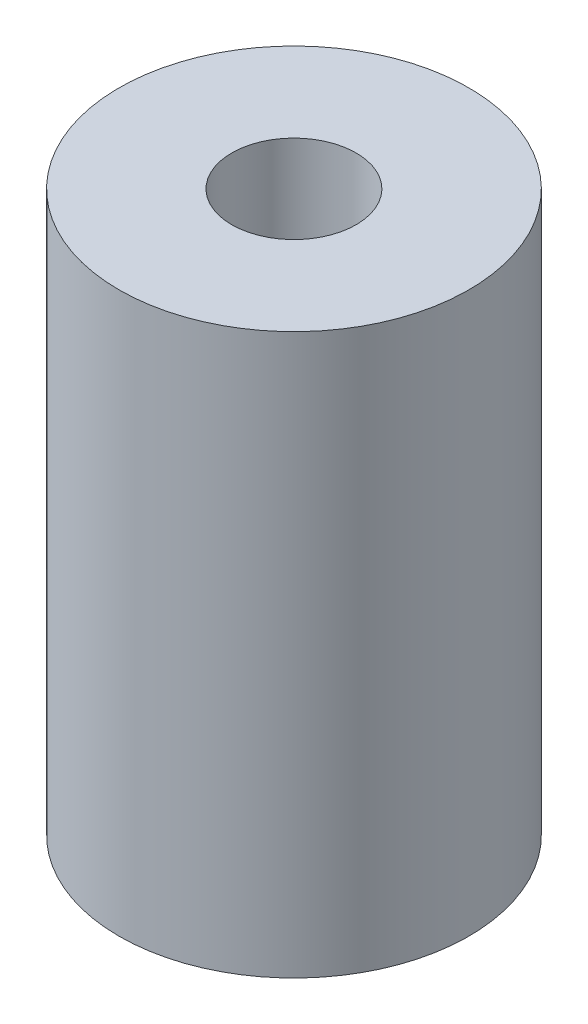
SolidWorks part; units mm, degrees
ref_plane "Front Plane" through (0, 0, 0) normal (0, 0, 1) x (1, 0, 0)
ref_plane "Top Plane" through (0, 0, 0) normal (0, 1, 0) x (1, 0, 0)
ref_plane "Right Plane" through (0, 0, 0) normal (1, 0, 0) x (0, 0, -1)
sketch "Sketch1" plane through (0, 0, 0) normal (0, 1, 0) x (1, 0, 0)
  circle A0 centre (0, 0) radius 4.5
  circle A1 centre (0, 0) radius 1.6
  dimension "D1" = 9
  dimension "D2" = 3.2
extrude "Boss-Extrude1" add sketch "Sketch1" along normal blind 14.4
